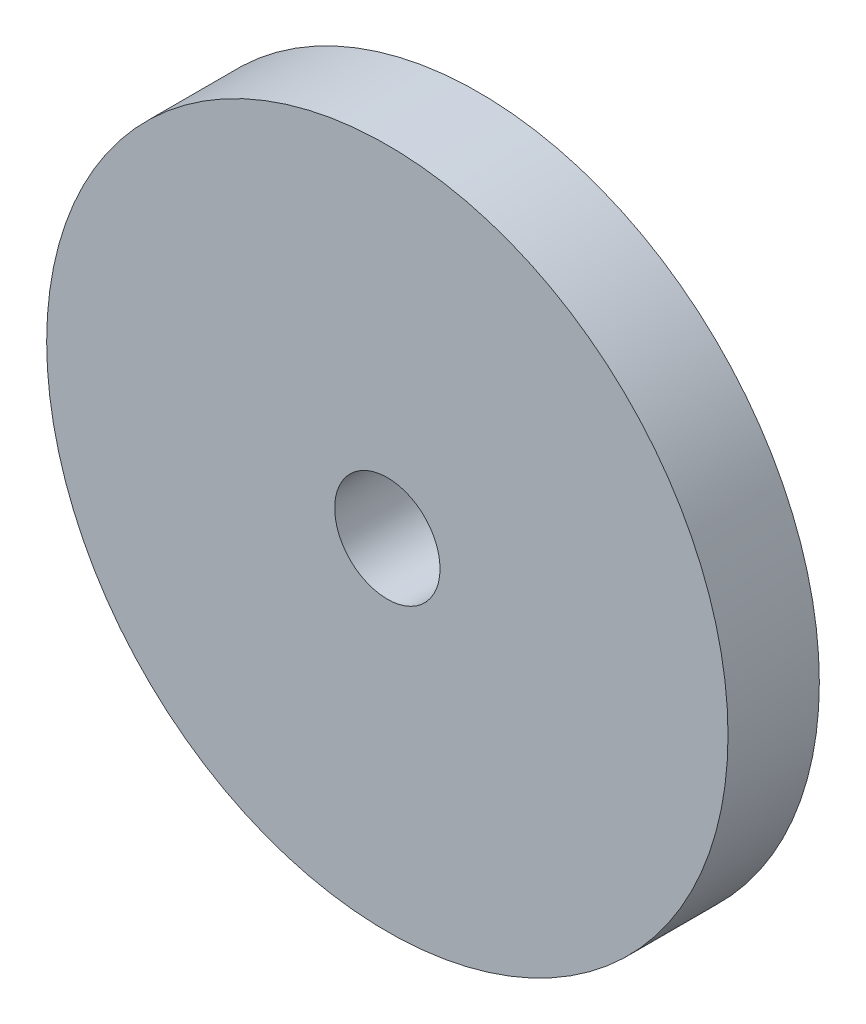
SolidWorks part; units mm, degrees
material "Настроенная пользователем пластмасса"
ref_plane "Спереди" through (0, 0, 0) normal (0, 0, 1) x (1, 0, 0)
ref_plane "Сверху" through (0, 0, 0) normal (0, 1, 0) x (1, 0, 0)
ref_plane "Справа" through (0, 0, 0) normal (1, 0, 0) x (0, 0, -1)
sketch "Эскиз1" plane through (0, 0, 0) normal (0, 1, 0) x (1, 0, 0)
  line L0 (5, 0) -> (5, 1)
  line L1 (5, 1) -> (3.75, 1)
  line L2 (3.75, 1) -> (3.75, -6.5)
  line L3 (3.75, -6.5) -> (24.25, -6.5)
  line L4 (24.25, -6.5) -> (24.25, 0)
  line L5 (24.25, 0) -> (5, 0)
  line L6 (0, 1) -> (0, -6.5) construction
revolve "Повернуть1" add sketch "Эскиз1" angle 360 about L6
